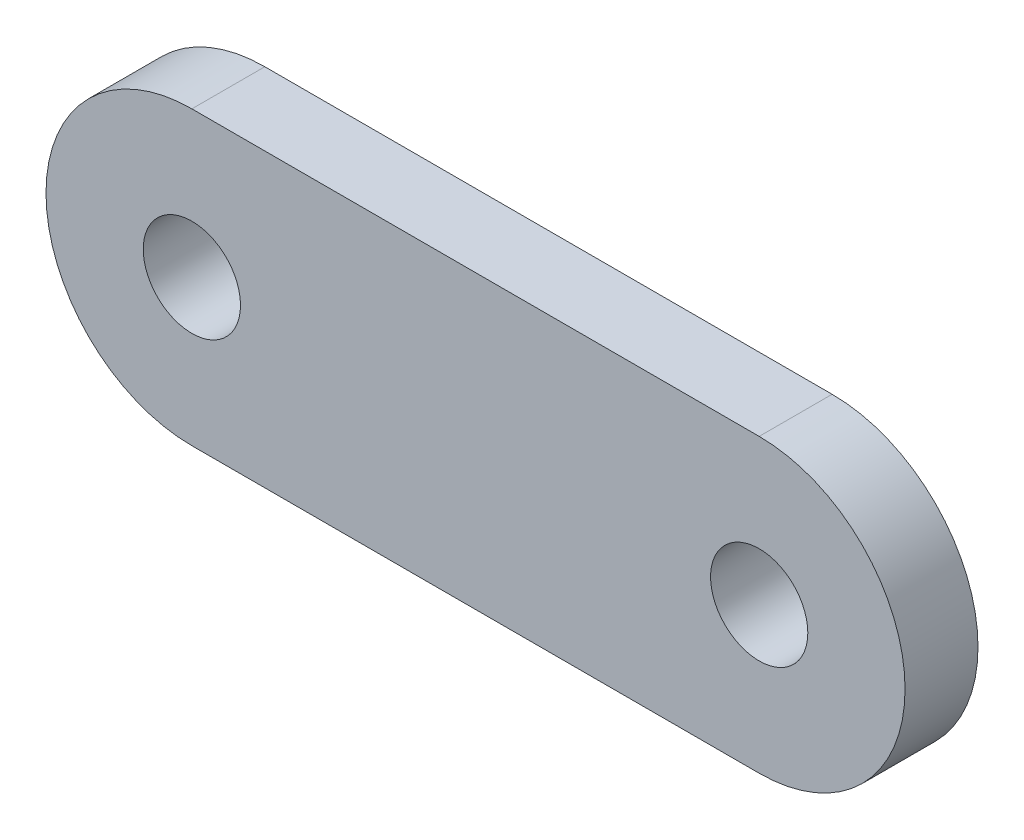
SolidWorks part; units mm, degrees
ref_plane "Front Plane" through (0, 0, 0) normal (0, 0, 1) x (1, 0, 0)
ref_plane "Top Plane" through (0, 0, 0) normal (0, 1, 0) x (1, 0, 0)
ref_plane "Right Plane" through (0, 0, 0) normal (1, 0, 0) x (0, 0, -1)
sketch "Sketch1" plane through (0, 0, 0) normal (0, 0, 1) x (1, 0, 0)
  line L0 (-35.3127, 0) -> (-11.9786, 0) construction
  line L1 (-35.3127, 6) -> (-11.9786, 6)
  line L2 (-35.3127, -6) -> (-11.9786, -6)
  arc A0 (-35.3127, 6) -> (-35.3127, -6) centre (-35.3127, 0) ccw
  arc A1 (-11.9786, -6) -> (-11.9786, 6) centre (-11.9786, 0) ccw
  circle A2 centre (-35.3127, 0) radius 2
  circle A3 centre (-11.9786, 0) radius 2
  point P3 (-23.6457, 0)
  dimension "D3" = 4
  dimension "D4" = 4
  dimension "D1" = 23.3341
  dimension "D2" = 12
extrude "Boss-Extrude3" add sketch "Sketch1" along normal blind 3
